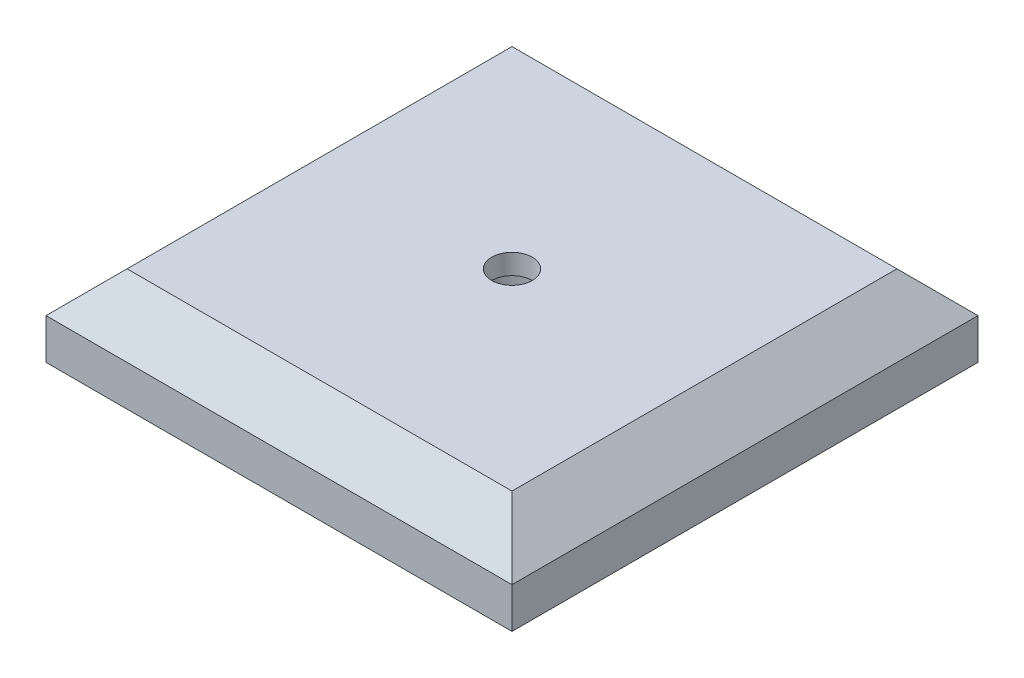
SolidWorks part; units mm, degrees
ref_plane "Front Plane" through (0, 0, 0) normal (0, 0, 1) x (1, 0, 0)
ref_plane "Top Plane" through (0, 0, 0) normal (0, 1, 0) x (1, 0, 0)
ref_plane "Right Plane" through (0, 0, 0) normal (1, 0, 0) x (0, 0, -1)
sketch "Sketch1" plane through (0, 0, 0) normal (0, 1, 0) x (1, 0, 0)
  line L1 (-1.4375, -1.4375) -> (1.4375, -1.4375)
  line L2 (-1.4375, -1.4375) -> (-1.4375, 1.4375)
  line L3 (-1.4375, 1.4375) -> (1.4375, 1.4375)
  line L4 (1.4375, -1.4375) -> (1.4375, 1.4375)
  line L5 (-1.4375, -1.4375) -> (1.4375, 1.4375) construction
  line L6 (-1.4375, 1.4375) -> (1.4375, -1.4375) construction
  point P0 (0, 0)
extrude "Boss-Extrude1" add sketch "Sketch1" along normal blind 0.5
sketch "Sketch2" plane through (0, 0.5, 0) normal (0, 1, 0) x (1, 0, 0)
  circle A0 centre (0, 0) radius 0.125
  dimension "D1" = 0.25
extrude "Cut-Extrude1" cut sketch "Sketch2" against normal blind 0.125
sketch "Sketch3" plane through (0, 0, 0) normal (0, -1, 0) x (1, 0, 0)
  circle A0 centre (0, 0) radius 0.25
  dimension "D1" = 0.5
extrude "Cut-Extrude2" cut sketch "Sketch3" against normal blind 0.375
chamfer "Chamfer2" distance 0.25 4 edges at (-1.4375, 0.5, 0) (0, 0.5, 1.4375) (1.4375, 0.5, 0) (0, 0.5, -1.4375)
